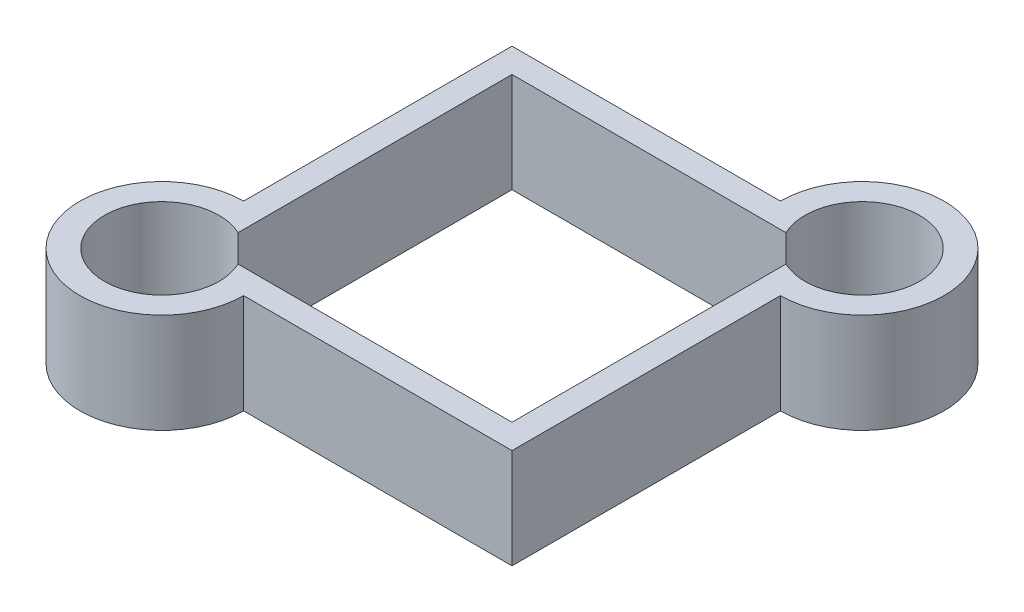
SolidWorks part; units mm, degrees
ref_plane "Front Plane" through (0, 0, 0) normal (0, 0, 1) x (1, 0, 0)
ref_plane "Top Plane" through (0, 0, 0) normal (0, 1, 0) x (1, 0, 0)
ref_plane "Right Plane" through (0, 0, 0) normal (1, 0, 0) x (0, 0, -1)
sketch "Sketch1" plane through (0, 0, 0) normal (0, 1, 0) x (1, 0, 0)
  line L0 (-92, 92) -> (75.3772, 92)
  line L1 (-107, 107) -> (57, 107)
  line L2 (-107, 107) -> (-107, -57)
  line L3 (-57, -107) -> (107, -107)
  line L4 (107, 57) -> (107, -107)
  line L5 (-107, 107) -> (107, -107) construction
  line L6 (-107, -107) -> (107, 107) construction
  line L7 (92, 75.3772) -> (92, -92)
  line L8 (-75.3772, -92) -> (92, -92)
  line L9 (-92, 92) -> (-92, -75.3772)
  line L11 (-107, 107) -> (-107, -107) construction
  line L12 (-107, -107) -> (107, -107) construction
  line L13 (-92, -92) -> (92, -92) construction
  line L14 (-92, 92) -> (-92, -92) construction
  line L15 (-92, 92) -> (92, 92) construction
  line L16 (92, 92) -> (92, -92) construction
  line L17 (-107, 107) -> (107, 107) construction
  line L18 (107, 107) -> (107, -107) construction
  arc A0 (107, 57) -> (57, 107) centre (107, 107) ccw
  arc A1 (92, 75.3772) -> (75.3772, 92) centre (107, 107) ccw
  arc A2 (-92, -75.3772) -> (-75.3772, -92) centre (-107, -107) ccw
  arc A3 (-107, -57) -> (-57, -107) centre (-107, -107) ccw
  point P0 (0, 0)
  point P10 (0, 0)
  point P13 (0, 0)
  point P20 (0, 0)
  dimension "D4" = 70
  dimension "D1" = 214
  dimension "D2" = 214
  dimension "D3" = 15
extrude "Boss-Extrude1" add sketch "Sketch1" along normal blind 61 contours L9 A2 L8 L7 A1 L0 | L2 A3 L3 L4 A0 L1 A2 L9 L0 A1 L7 L8
